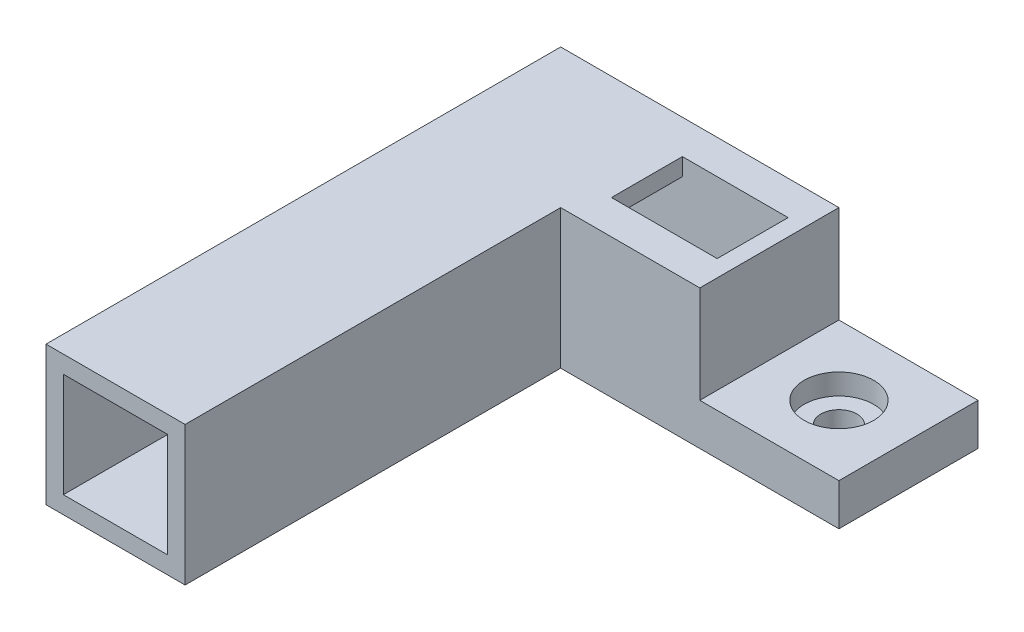
SolidWorks part; units mm, degrees
ref_plane "前视基准面" through (0, 0, 0) normal (0, 0, 1) x (1, 0, 0)
ref_plane "上视基准面" through (0, 0, 0) normal (0, 1, 0) x (1, 0, 0)
ref_plane "右视基准面" through (0, 0, 0) normal (1, 0, 0) x (0, 0, -1)
other "Configuration Table"
sketch "草图1" plane through (0, 0, 0) normal (0, 1, 0) x (1, 0, 0)
  line L5 (-30, 10) -> (30, 10)
  line L6 (-30, 10) -> (-30, -10)
  line L7 (-30, -10) -> (30, -10)
  line L8 (30, 10) -> (30, -10)
extrude "凸台-拉伸1" add sketch "草图1" along normal blind 6 contours L6 L5 L8 L7
sketch "草图2" plane through (0, 6, 0) normal (0, 1, 0) x (1, 0, 0)
  line L0 (0, 0) -> (10, 0)
  line L1 (10, 0) -> (30, 0)
  line L2 (30, 10) -> (30, -10) construction
  circle A0 centre (20, 0) radius 2.6
extrude "切除-拉伸1" cut sketch "草图2" against normal blind 6 contours L1 A0 | L1 A0
sketch "草图3" plane through (0, 6, 0) normal (0, 1, 0) x (1, 0, 0)
  circle A0 centre (20, 0) radius 5
extrude "切除-拉伸2" cut sketch "草图3" against normal blind 3
sketch "草图4" plane through (0, 6, 0) normal (0, 1, 0) x (1, 0, 0)
  line L1 (-30, -10) -> (30, -10) construction
  line L2 (0, -10) -> (10, -10)
  line L4 (-30, 10) -> (30, 10) construction
  line L5 (0, 10) -> (-10, 10)
  line L7 (-10, 10) -> (10, 10)
  line L8 (-10, 10) -> (-10, -10)
  line L9 (-10, -10) -> (10, -10)
  line L10 (10, 10) -> (10, -10)
  line M8 (-30, -10) -> (30, -10)
  line M10 (30, 10) -> (-30, 10)
extrude "凸台-拉伸2" add sketch "草图4" along normal blind 14 contours L10 L8 M10 M8
sketch "草图5" plane through (0, 20, 0) normal (0, 1, 0) x (1, 0, 0)
  line L0 (0, 0) -> (7.6, 0)
  line L1 (7.6, 0) -> (7.6, -5.1)
  line L2 (0, 0) -> (-7.6, 0)
  line L3 (-7.6, 0) -> (-7.6, 5.1)
  line L5 (-7.6, 5.1) -> (7.6, 5.1)
  line L6 (-7.6, 5.1) -> (-7.6, -5.1)
  line L7 (-7.6, -5.1) -> (7.6, -5.1)
  line L8 (7.6, 5.1) -> (7.6, -5.1)
extrude "切除-拉伸3" cut sketch "草图5" against normal blind 20 contours L8 L5 L3 L2 L0 | L6 L7 L1 L0 L2
sketch "草图6" plane through (0, 6, 0) normal (0, 1, 0) x (1, 0, 0)
  line L1 (-30, 10) -> (-10, 10)
  line L2 (-30, 10) -> (-30, -10)
  line L3 (-30, -10) -> (-10, -10)
  line L4 (-10, 10) -> (-10, -10)
extrude "凸台-拉伸3" add sketch "草图6" along normal blind 14 contours L2 L1 L4 L3
sketch "草图7" plane through (0, 0, 10) normal (0, 0, 1) x (1, 0, 0)
  line L0 (-30, 0) -> (30, 0) construction
  line L1 (-30, 20) -> (-10, 20)
  line L2 (-30, 20) -> (-30, 0)
  line L3 (-30, 0) -> (-10, 0)
  line L4 (-10, 20) -> (-10, 0)
extrude "凸台-拉伸4" add sketch "草图7" along normal blind 54
sketch "草图8" plane through (0, 0, 64) normal (0, 0, 1) x (1, 0, 0)
  line L0 (-30, 20) -> (-27.5, 20)
  line L1 (-10, 20) -> (-30, 20) construction
  line L2 (-27.5, 20) -> (-27.5, 17.5)
  line L3 (-10, 0) -> (-12.5, 0)
  line L4 (-30, 0) -> (-10, 0) construction
  line L5 (-12.5, 0) -> (-12.5, 2.5)
  line L7 (-27.5, 17.5) -> (-12.5, 17.5)
  line L8 (-27.5, 17.5) -> (-27.5, 2.5)
  line L9 (-27.5, 2.5) -> (-12.5, 2.5)
  line L10 (-12.5, 17.5) -> (-12.5, 2.5)
extrude "切除-拉伸4" cut sketch "草图8" against normal blind 64 contours L10 L7 L8 L9
sketch "草图9" plane through (0, 20, 0) normal (0, 1, 0) x (1, 0, 0)
  line L0 (-7.6, -5.1) -> (-30, -5.1)
  line L1 (-30, 10) -> (-30, -64) construction
  line L2 (-30, -5.1) -> (-30, 5.1)
  line L3 (-30, 5.1) -> (-27.5, 5.1)
  line L5 (-27.5, 5.1) -> (-7.6, 5.1)
  line L6 (-27.5, 5.1) -> (-27.5, -5.1)
  line L7 (-27.5, -5.1) -> (-7.6, -5.1)
  line L8 (-7.6, 5.1) -> (-7.6, -5.1)
  line M12 (-7.6, -5.1) -> (-7.6, 5.1)
extrude "切除-拉伸5" cut sketch "草图9" against normal blind 17.5 contours L5 L6 L0 M12
sketch "草图11" plane through (0, 2.5, 0) normal (0, 1, 0) x (1, 0, 0)
  line L1 (-27.5, 5.1) -> (-7.6, 5.1)
  line L2 (-27.5, 5.1) -> (-27.5, -5.1)
  line L3 (-27.5, -5.1) -> (-7.6, -5.1)
  line L4 (-7.6, 5.1) -> (-7.6, -5.1)
extrude "切除-拉伸6" cut sketch "草图11" against normal blind 15 contours L2 L1 L4 L3
sketch "草图12" plane through (0, 20, 0) normal (0, 1, 0) x (1, 0, 0)
  line L1 (-27.5, 5.1) -> (7.6, 5.1)
  line L2 (-27.5, 5.1) -> (-27.5, -5.1)
  line L3 (-27.5, -5.1) -> (7.6, -5.1)
  line L4 (7.6, 5.1) -> (7.6, -5.1)
extrude "凸台-拉伸5" add sketch "草图12" against normal blind 2.5
sketch "草图13" plane through (0, 20, 0) normal (0, 1, 0) x (1, 0, 0)
  line L0 (0, 0) -> (7.6, 0)
  line L1 (0, 0) -> (-7.6, 0)
  line L2 (-7.6, 0) -> (-7.6, 5.1)
  line L3 (7.6, 0) -> (7.6, -5.1)
  line L5 (-7.6, 5.1) -> (7.6, 5.1)
  line L6 (-7.6, 5.1) -> (-7.6, -5.1)
  line L7 (-7.6, -5.1) -> (7.6, -5.1)
  line L8 (7.6, 5.1) -> (7.6, -5.1)
extrude "切除-拉伸7" cut sketch "草图13" against normal blind 2.5 contours L8 L5 L2 L1 L0 | L6 L7 L3 L0 L1
